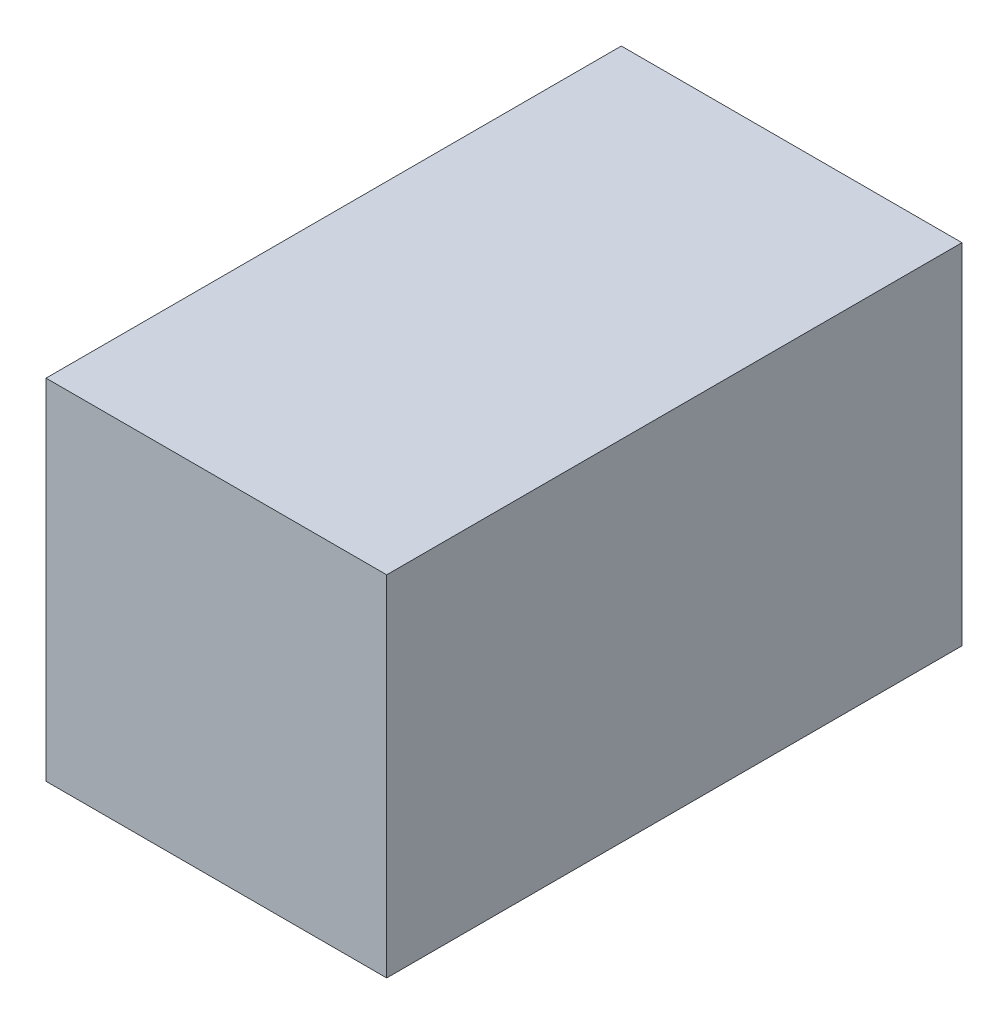
SolidWorks part; units mm, degrees
ref_plane "Front Plane" through (0, 0, 0) normal (0, 0, 1) x (1, 0, 0)
ref_plane "Top Plane" through (0, 0, 0) normal (0, 1, 0) x (1, 0, 0)
ref_plane "Right Plane" through (0, 0, 0) normal (1, 0, 0) x (0, 0, -1)
sketch "Sketch1" plane through (0, 0, 0) normal (0, 0, 1) x (1, 0, 0)
  line L0 (-1.8542, 3.6196) -> (5.2578, 3.6196)
  line L1 (5.2578, 3.6196) -> (5.2578, -3.6704)
  line L2 (5.2578, -3.6704) -> (-1.8542, -3.6704)
  line L3 (-1.8542, -3.6704) -> (-1.8542, 3.6196)
extrude "Component_Outline" add sketch "Sketch1" along normal blind 12.01 separate body
sketch3d "3DSketch1"
  line L0 (0, 0, 0) -> (1, 0, 0)
  line L1 (0, 0, 0) -> (0, 1, 0)
  line L2 (0, 0, 0) -> (0, 0, 1)
  point P0 (0, 0, 0)
